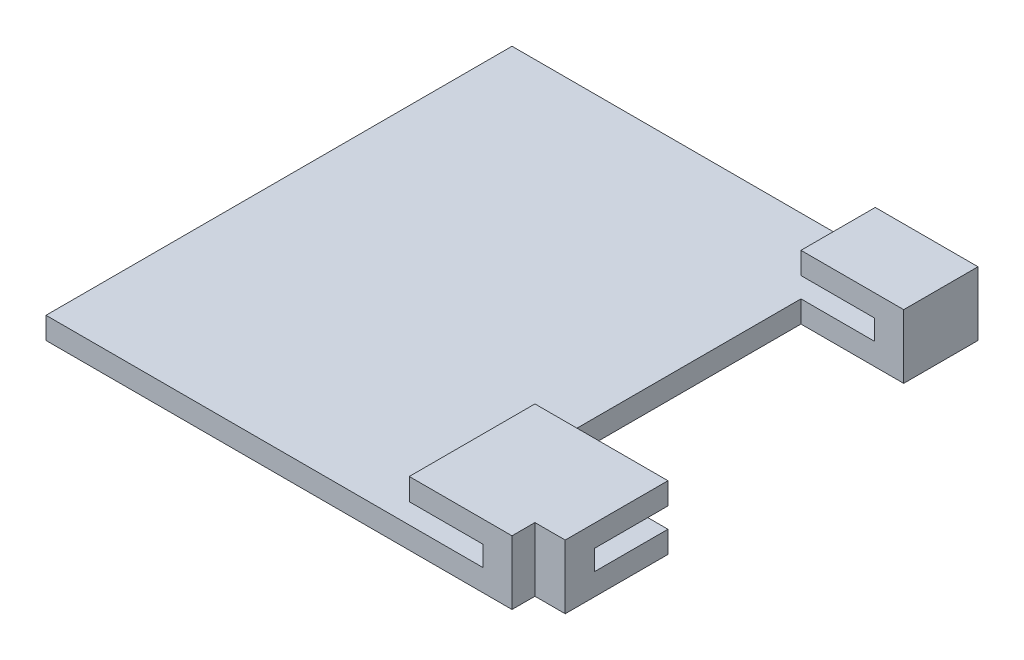
SolidWorks part; units mm, degrees
ref_plane "Front Plane" through (0, 0, 0) normal (0, 0, 1) x (1, 0, 0)
ref_plane "Top Plane" through (0, 0, 0) normal (0, 1, 0) x (1, 0, 0)
ref_plane "Right Plane" through (0, 0, 0) normal (1, 0, 0) x (0, 0, -1)
sketch "Sketch1" plane through (0, 0, 0) normal (0, 0, 1) x (1, 0, 0)
  line L0 (0, 0) -> (8.025, 0)
  line L1 (8.025, 0) -> (8.025, -2.2)
  line L2 (8.025, -2.2) -> (-39.6, -2.2)
  line L3 (-39.6, -2.2) -> (-39.6, -4.5812)
  line L4 (-39.6, -4.5812) -> (11.2, -4.5812)
  line L5 (11.2, -4.5812) -> (11.2, 2.3813)
  line L6 (11.2, 2.3813) -> (0, 2.3813)
  line L7 (0, 2.3813) -> (0, 0)
  line L8 (-14.2, -4.5812) -> (-14.2, 1.7415) construction
  dimension "D1" = 2.3813
  dimension "d2" = 8.025
  dimension "D3" = 2.2
  dimension "D4" = 11.2
  dimension "D5" = 6.9625
  dimension "D6" = 25.4
extrude "Boss-Extrude1" add sketch "Sketch1" along normal mid plane 50.8
sketch "Sketch2" plane through (0, 2.3813, 0) normal (0, 1, 0) x (1, 0, 0)
  line L0 (11.2, -25.4) -> (11.2, 25.4) construction
  line L1 (11.2, 11.7) -> (0, 11.7)
  line L2 (11.2, 11.7) -> (11.2, -11.7)
  line L3 (11.2, -11.7) -> (0, -11.7)
  line L4 (0, 11.7) -> (0, -11.7)
  line L5 (11.2, 11.7) -> (0, -11.7) construction
  line L6 (11.2, -11.7) -> (0, 11.7) construction
  line L7 (0, -25.4) -> (0, 25.4) construction
  line L10 (0, 11.7) -> (0, 17.3)
  line L11 (0, 17.3) -> (11.2, 17.3)
  line L12 (11.2, 11.7) -> (11.2, 17.3)
  line L13 (0, 11.7) -> (11.2, 17.3) construction
  line L14 (0, 17.3) -> (11.2, 11.7) construction
  point P4 (5.6, 0)
  point P12 (5.6, 14.5)
  line M7 (0, 25.4) -> (0, -25.4)
  line M9 (11.2, -25.4) -> (11.2, 25.4)
  dimension "D1" = 23.4
extrude "Cut-Extrude1" cut sketch "Sketch2" against normal through all contours L3 L1 M9 M7 | L11 L1 M7 M9
sketch "Sketch3" plane through (11.2, 0, 0) normal (-1, 0, 0) x (0, 0, 1)
  line L0 (25.4, 2.3813) -> (11.7, 2.3813) construction
  line L1 (11.7, 0) -> (22.9, 0)
  line L2 (11.7, 0) -> (11.7, 2.3813)
  line L3 (11.7, 2.3813) -> (22.9, 2.3813)
  line L4 (22.9, 0) -> (22.9, 2.3813)
  line L5 (11.7, 0) -> (22.9, 2.3813) construction
  line L6 (11.7, 2.3813) -> (22.9, 0) construction
  line L7 (22.9, 0) -> (22.9, -4.5812)
  line L8 (25.4, -4.5812) -> (11.7, -4.5812) construction
  line L9 (22.9, -4.5812) -> (11.7, -4.5812)
  line L10 (11.7, -4.5812) -> (11.7, -2.2)
  line L11 (11.7, -4.5812) -> (11.7, 2.3813) construction
  line L12 (11.7, -2.2) -> (19.725, -2.2)
  line L13 (19.725, -2.2) -> (19.725, 0)
  point P4 (17.3, 1.1906)
  line M9 (11.7, -4.5812) -> (11.7, 2.3813)
  line M10 (11.7, 2.3813) -> (25.4, 2.3813)
  line M12 (25.4, -4.5812) -> (11.7, -4.5812)
  dimension "D1" = 11.2
  dimension "D2" = 2.2
  dimension "D3" = 3.175
extrude "Boss-Extrude2" add sketch "Sketch3" against normal blind 3.302 contours L12 L13 L1 L7 M12 M9 | L4 L1 M9 M10
sketch "Sketch4" plane through (0, 0, 11.7) normal (0, 0, -1) x (-1, 0, 0)
  line L1 (-11.2, 0) -> (-8.025, 0)
  line L2 (-11.2, 0) -> (-11.2, -2.2)
  line L3 (-11.2, -2.2) -> (-8.025, -2.2)
  line L4 (-8.025, 0) -> (-8.025, -2.2)
  line L5 (-11.2, 0) -> (-8.025, -2.2) construction
  line L6 (-11.2, -2.2) -> (-8.025, 0) construction
  point P4 (-9.6125, -1.1)
extrude "Cut-Extrude2" cut sketch "Sketch4" against normal up to surface (8.025 mm away) up to face at (12.851, -1.1, 19.725)
sketch "Sketch5" plane through (0, -2.2, 0) normal (0, 1, 0) x (1, 0, 0)
  line L0 (-15.575, 25.4) -> (-15.575, 3.875) construction
  line L1 (8.025, 25.4) -> (-39.6, 25.4) construction
  line L2 (-15.575, 3.875) -> (-39.6, 3.875) construction
  line L3 (-39.6, -25.4) -> (-39.6, 25.4) construction
  line L4 (-39.6, -19.725) -> (-15.575, -19.725) construction
  line L5 (-15.575, -19.725) -> (-15.575, -25.4) construction
  line L6 (8.025, -25.4) -> (-39.6, -25.4) construction
  line L7 (8.025, 25.4) -> (8.025, 3.875) construction
  line L8 (8.025, 3.875) -> (21.3267, 3.875) construction
  line L9 (8.025, -25.4) -> (8.025, -19.725) construction
  line L10 (8.025, -19.725) -> (21.3267, -19.725) construction
  line L11 (14.502, -19.725) -> (8.025, -19.725) construction
  line L13 (8.025, -25.4) -> (8.025, -19.725) construction
  dimension "D1" = 23.6
  dimension "D2" = 23.6
  dimension "D3" = 23.6
equation "\"lip depth\"= 11.2mm"
equation "\"lip thickness\"= 1.4mm"
equation "\"D3@Sketch1\"=\"lip thickness\"+.8mm"
equation "\"d2@Sketch1\"=\"lip depth\"-.125"
equation "\"D4@Sketch1\"=\"lip depth\""
equation "\"D5@Sketch1\"=0.09375*2 + .8mm + \"lip thickness\""
equation "\"D1@Sketch2\"=2*\"lip depth\"+1mm"
equation "\"D1@Sketch3\"=\"lip depth\""
equation "\"D1@Boss-Extrude2\"=\"lip depth\""
equation "\"D2@Sketch2\"=0.5*\"lip depth\""
equation "\"D2@Sketch3\"=\"lip thickness\"+.8mm"
